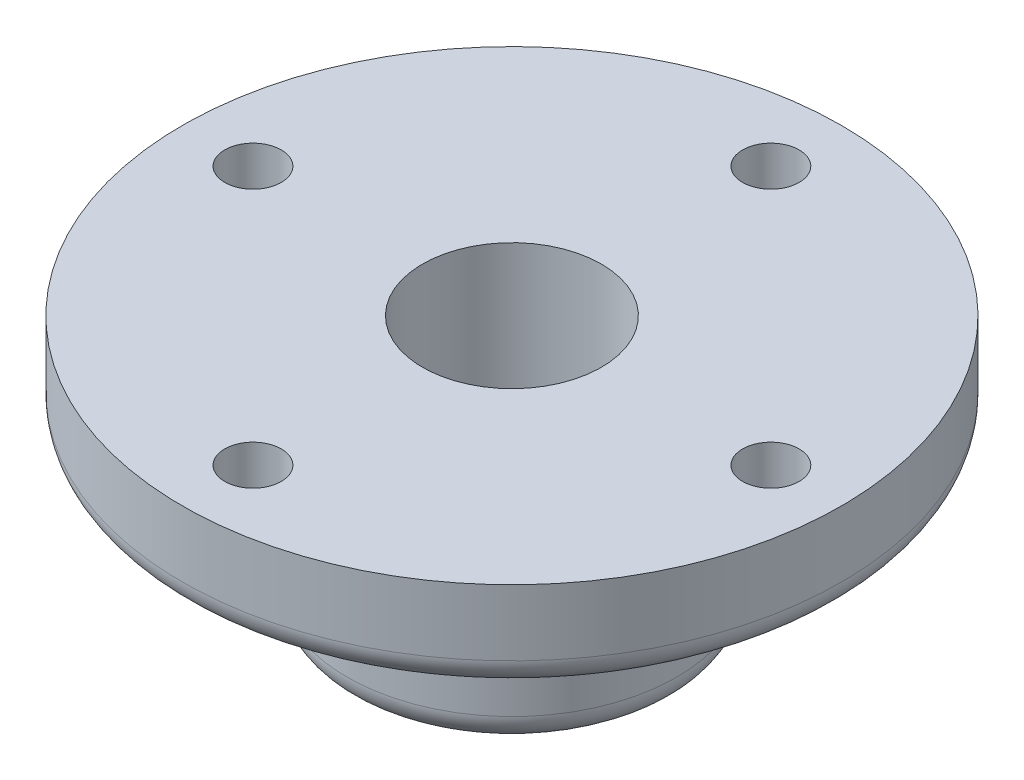
SolidWorks part; units mm, degrees
ref_plane "Alzado" through (0, 0, 0) normal (0, 0, 1) x (1, 0, 0)
ref_plane "Planta" through (0, 0, 0) normal (0, 1, 0) x (1, 0, 0)
ref_plane "Vista lateral" through (0, 0, 0) normal (1, 0, 0) x (0, 0, -1)
sketch "Croquis1" plane through (0, 0, 0) normal (0, 0, 1) x (1, 0, 0)
  line L0 (0, 0) -> (0, 120.6119) construction
  line L1 (70, 69.2961) -> (70, 49.2961)
  line L2 (70, 49.2961) -> (35, 49.2961)
  line L3 (35, 49.2961) -> (35, 14.2961)
  line L4 (35, 14.2961) -> (19, 14.2961)
  line L5 (19, 14.2961) -> (19, 69.2961)
  line L6 (19, 69.2961) -> (70, 69.2961)
  dimension "D1" = 20
  dimension "D2" = 55
  dimension "D3" = 140
  dimension "D4" = 38
  dimension "D5" = 70
revolve "Revolución1" add sketch "Croquis1" angle 360 about L0
sketch "Croquis2" plane through (0, 49.2961, 0) normal (0, -1, 0) x (1, 0, 0)
  circle A1 centre (0, 55) radius 6
  dimension "D1" = 55
  dimension "D2" = 12
extrude "Cortar-Extruir1" cut sketch "Croquis2" against normal up to next
pattern_circular "MatrizC1" count 4 over 360 about axis through (0, 0, 0) along (0, 1, 0) of "Cortar-Extruir1"
fillet "Redondeo1" radius 6 3 edges at (0, 49.2961, -70) (0, 14.2961, -35) (0, 49.2961, -35)
